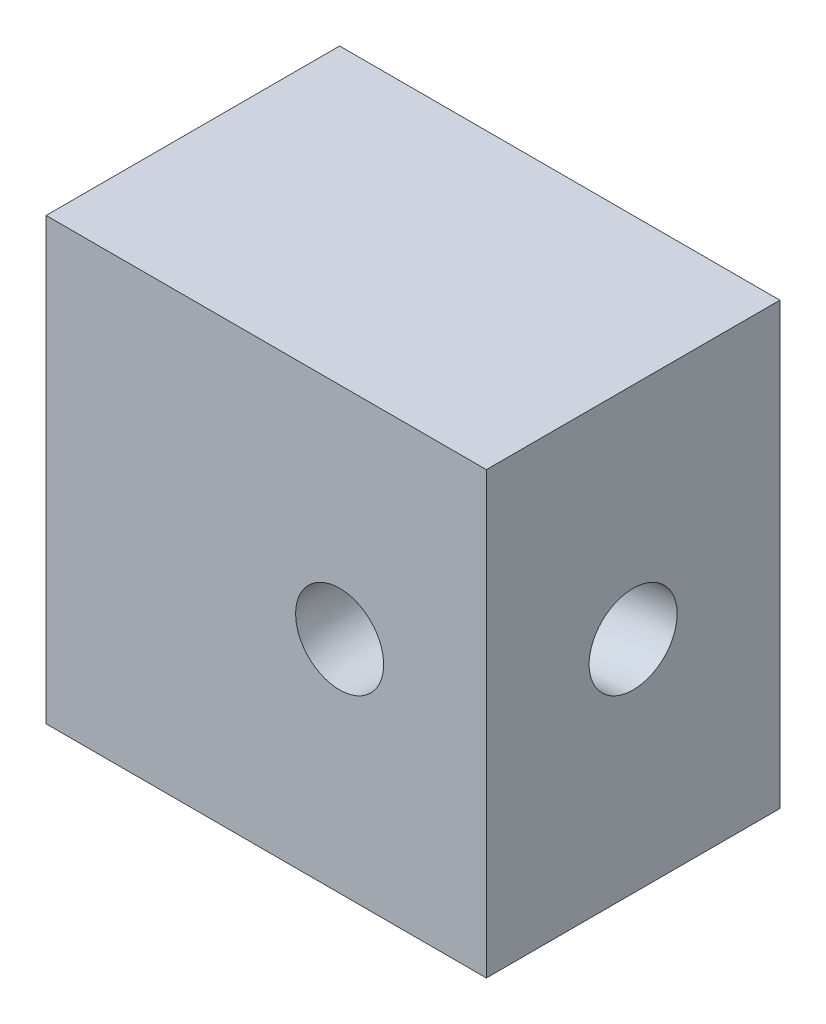
SolidWorks part; units mm, degrees
ref_plane "Front Plane" through (0, 0, 0) normal (0, 0, 1) x (1, 0, 0)
ref_plane "Top Plane" through (0, 0, 0) normal (0, 1, 0) x (1, 0, 0)
ref_plane "Right Plane" through (0, 0, 0) normal (1, 0, 0) x (0, 0, -1)
sketch "Sketch2" plane through (0, 0, 0) normal (0, 0, 1) x (1, 0, 0)
  line L1 (-38.1, 38.1) -> (38.1, 38.1)
  line L2 (-38.1, 38.1) -> (-38.1, -38.1)
  line L3 (-38.1, -38.1) -> (38.1, -38.1)
  line L4 (38.1, 38.1) -> (38.1, -38.1)
  line L5 (0, -38.1) -> (0, 38.1) construction
  line L6 (-38.1, 0) -> (38.1, 0) construction
  point P0 (0, 0)
  dimension "D1" = 76.2
  dimension "D2" = 76.2
extrude "Boss-Extrude1" add sketch "Sketch2" along normal blind 50.8
sketch "Sketch3" plane through (0, 0, 50.8) normal (0, 0, 1) x (1, 0, 0)
  line L0 (38.1, -38.1) -> (38.1, 38.1) construction
  line L1 (38.1, 38.1) -> (-38.1, 38.1) construction
  circle A0 centre (12.7, 0) radius 7.62
  point P6 (30.1416, 16.2927)
  dimension "D1" = 15.24
  dimension "D2" = 25.4
  dimension "D3" = 38.1
revolve "Cut-Revolve1" cut sketch "Sketch3" angle 360 about axis through (38.1, 38.1, 50.8) along (0, 1, 0)
